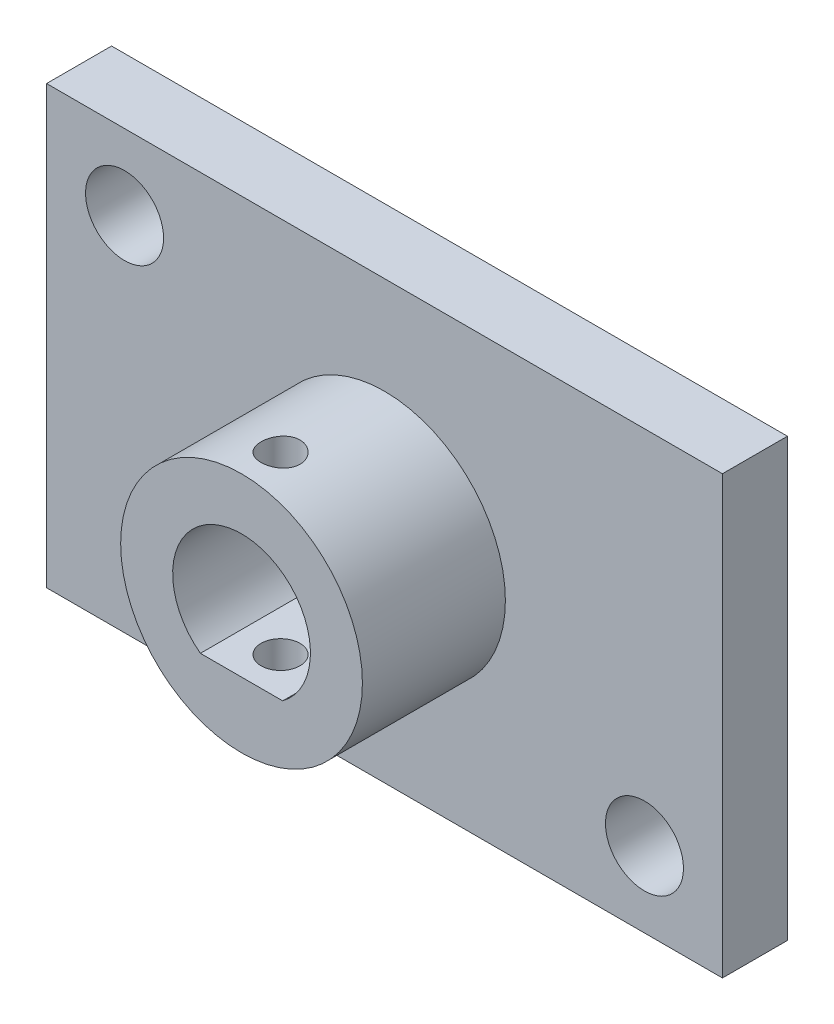
SolidWorks part; units mm, degrees
ref_plane "前视基准面" through (0, 0, 0) normal (0, 0, 1) x (1, 0, 0)
ref_plane "上视基准面" through (0, 0, 0) normal (0, 1, 0) x (1, 0, 0)
ref_plane "右视基准面" through (0, 0, 0) normal (1, 0, 0) x (0, 0, -1)
sketch "草图1" plane through (0, 0, 0) normal (0, 0, 1) x (1, 0, 0)
  line L1 (-26, -16.8) -> (26, -16.8)
  line L2 (-26, -16.8) -> (-26, 16.8)
  line L3 (-26, 16.8) -> (26, 16.8)
  line L4 (26, -16.8) -> (26, 16.8)
  line L5 (-26, -16.8) -> (26, 16.8) construction
  line L6 (-26, 16.8) -> (26, -16.8) construction
  point P0 (0, 0)
  dimension "D1" = 33.6
  dimension "D2" = 52
extrude "凸台-拉伸1" add sketch "草图1" along normal blind 5
sketch "草图3" plane through (0, 0, 5) normal (0, 0, 1) x (1, 0, 0)
  circle A0 centre (-20, 11) radius 3
  circle A1 centre (20, -11) radius 3
  dimension "D5" = 6
  dimension "D6" = 6
  dimension "D1" = 11
  dimension "D2" = 11
  dimension "D3" = 20
  dimension "D4" = 20
extrude "切除-拉伸2" cut sketch "草图3" against normal blind 5
sketch "草图4" plane through (0, 0, 5) normal (0, 0, 1) x (1, 0, 0)
  line L0 (3.1666, -4.25) -> (-3.1666, -4.25)
  circle A0 centre (0, 0) radius 9.3
  arc A1 (3.1666, -4.25) -> (-3.1666, -4.25) centre (0, 0) ccw
  dimension "D1" = 18.6
  dimension "D2" = 10.6
  dimension "D3" = 4.25
extrude "凸台-拉伸2" add sketch "草图4" along normal blind 11
sketch "草图5" plane through (0, 0, 0) normal (0, 1, 0) x (1, 0, 0)
  line L0 (-3.1666, -16) -> (3.1666, -16) construction
  circle A0 centre (0, -13) radius 1.5
  dimension "D1" = 3
  dimension "D2" = 3
extrude "切除-拉伸3" cut sketch "草图5" against normal blind 11 and the other way blind 11
